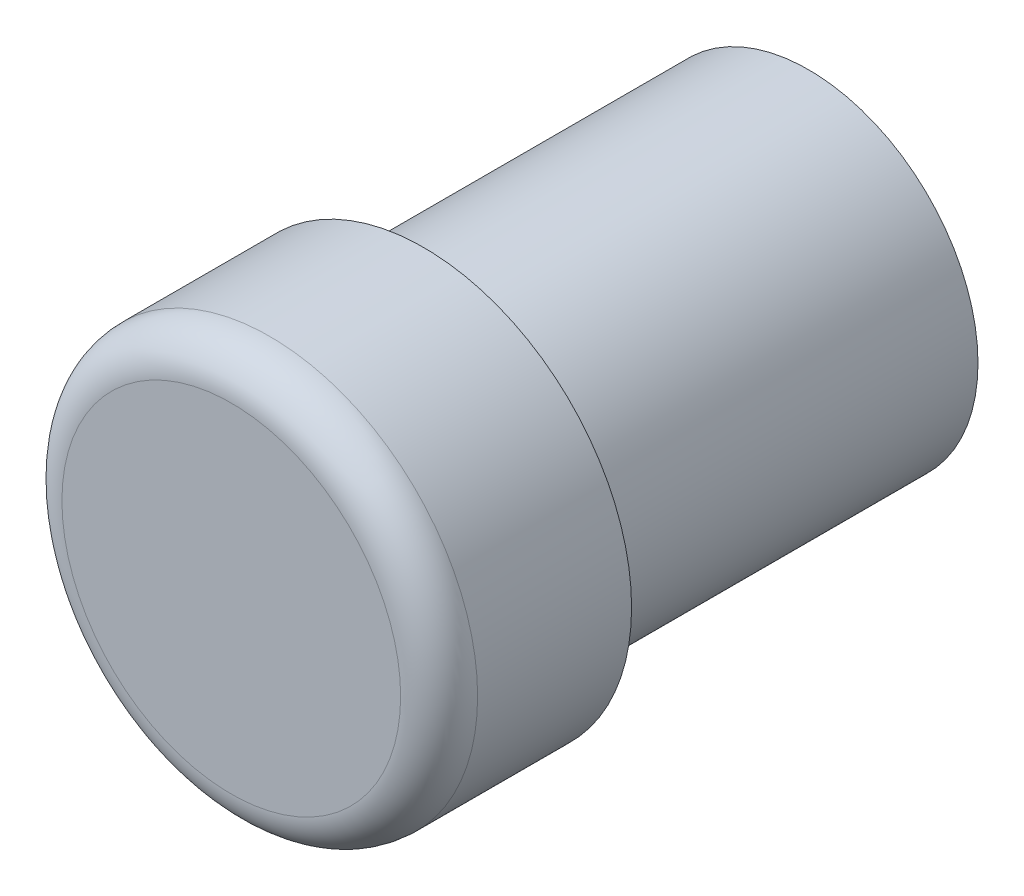
SolidWorks part; units mm, degrees
ref_plane "前视基准面" through (0, 0, 0) normal (0, 0, 1) x (1, 0, 0)
ref_plane "上视基准面" through (0, 0, 0) normal (0, 1, 0) x (1, 0, 0)
ref_plane "右视基准面" through (0, 0, 0) normal (1, 0, 0) x (0, 0, -1)
other "Configuration Table"
sketch "草图1" plane through (0, 0, 0) normal (0, 0, 1) x (1, 0, 0)
  circle A0 centre (0, 0) radius 10.8
  dimension "D1" = 21.6
extrude "凸台-拉伸1" add sketch "草图1" along normal blind 10 contours A0
sketch "草图2" plane through (0, 0, 0) normal (0, 0, -1) x (-1, 0, 0)
  circle A0 centre (0, 0) radius 8.8
  dimension "D1" = 17.6
extrude "凸台-拉伸2" add sketch "草图2" along normal blind 20
fillet "圆角1" radius 2 1 edges at (10.8, 0, 10)
sketch "草图3" plane through (0, 0, -20) normal (0, 0, -1) x (-1, 0, 0)
  circle A0 centre (0, 0) radius 2
  dimension "D1" = 4
extrude "切除-拉伸1" cut sketch "草图3" against normal blind 10
